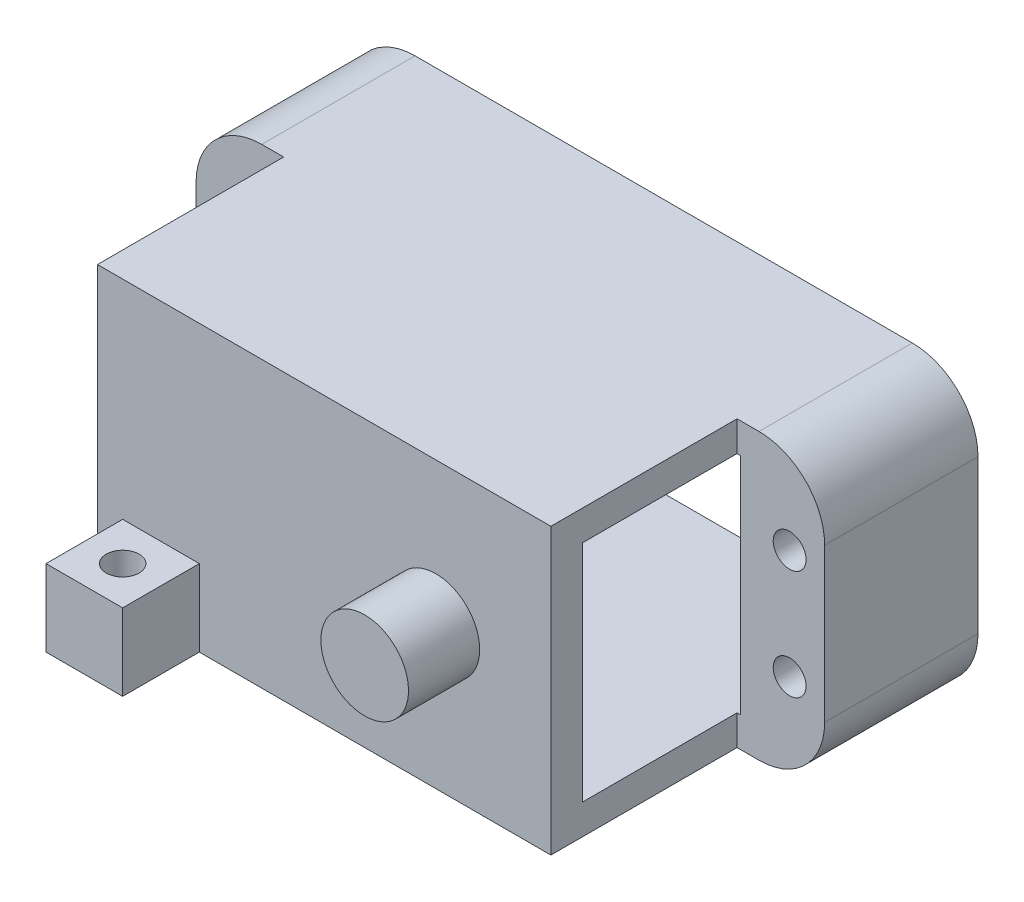
SolidWorks part; units mm, degrees
ref_plane "Front Plane" through (0, 0, 0) normal (0, 0, 1) x (1, 0, 0)
ref_plane "Top Plane" through (0, 0, 0) normal (0, 1, 0) x (1, 0, 0)
ref_plane "Right Plane" through (0, 0, 0) normal (1, 0, 0) x (0, 0, -1)
ref_plane "Plane4" through (0, 0, 0) normal (0, 0, -1) x (-1, 0, 0)
sketch "Sketch1" plane through (0, 0, 0) normal (0, 0, -1) x (-1, 0, 0)
  line L0 (-21, 13) -> (-21, -13)
  line L1 (-21, -13) -> (28.7, -13)
  line L2 (28.7, -13) -> (28.7, 13)
  line L3 (28.7, 13) -> (-21, 13)
extrude "Boss-Extrude1" add sketch "Sketch1" against normal blind 14
sketch "Sketch2" plane through (0, 0, 14) normal (0, 0, 1) x (1, 0, 0)
  line L0 (20.7, 13) -> (20.7, -13)
  line L1 (20.7, -13) -> (-20.7, -13)
  line L2 (-20.7, -13) -> (-20.7, 13)
  line L3 (-20.7, 13) -> (20.7, 13)
extrude "Boss-Extrude2" add sketch "Sketch2" along normal blind 17
ref_plane "Plane5" through (0, 10.25, 0) normal (0, 1, 0) x (1, 0, 0)
sketch "Sketch3" plane through (0, 10.25, 0) normal (0, 1, 0) x (1, 0, 0)
  line L0 (20.7, -14) -> (21, -14)
  line L1 (21, -14) -> (21, 0)
  line L2 (21, 0) -> (-21, 0)
  line L3 (-21, 0) -> (-21, -14)
  line L4 (-21, -14) -> (-20.7, -14)
  line L5 (-20.7, -14) -> (-20.7, -28.1)
  line L6 (-20.7, -28.1) -> (20.7, -28.1)
  line L7 (20.7, -28.1) -> (20.7, -14)
extrude "Cut-Extrude1" cut sketch "Sketch3" against normal blind 20.5
sketch "Sketch4" plane through (21, 0, 0) normal (1, 0, 0) x (0, 0, -1)
  line L0 (-14, -13) -> (-14, 13)
  line L1 (-14, 13) -> (0, 13)
  line L2 (0, 13) -> (0, -13)
  line L3 (0, -13) -> (-14, -13)
extrude "Boss-Extrude3" add sketch "Sketch4" along normal blind 7.7
sketch "Sketch5" plane through (0, 0, 31) normal (0, 0, 1) x (1, 0, 0)
  line L0 (-18.4, 13) -> (-11.4, 13)
  line L1 (-11.4, 13) -> (-11.4, 6)
  line L2 (-11.4, 6) -> (-18.4, 6)
  line L3 (-18.4, 6) -> (-18.4, 13)
  line L4 (0, 0) -> (-20.7, 0) construction
  line L5 (-20.7, 13) -> (-20.7, -13) construction
  line L6 (-18.4, -13) -> (-11.4, -13)
  line L7 (-18.4, -6) -> (-18.4, -13)
  line L8 (-11.4, -6) -> (-18.4, -6)
  line L9 (-11.4, -13) -> (-11.4, -6)
sketch "Sketch6" plane through (0, 13, 0) normal (0, 1, 0) x (-1, 0, 0)
  line L0 (10.4, 0) -> (2.4, 0)
  line L1 (2.4, 0) -> (2.4, 5)
  line L2 (2.4, 5) -> (10.4, 5)
  line L3 (10.4, 5) -> (10.4, 0)
extrude "Boss-Extrude5" add sketch "Sketch6" against normal blind 7 from surface at -26 starting at face at (0, -13, 14.75)
ref_plane "Plane6" through (0, 0, 0) normal (0, -1, 0) x (1, 0, 0)
extrude "Boss-Extrude6" add sketch "Sketch5" along normal blind 7 contours L7 L6 L9 L8
sketch "Sketch7" plane through (0, 0, 0) normal (0, -1, 0) x (1, 0, 0)
  line L0 (14.2, 37.5) -> (10.2, 37.5)
  line L1 (10.2, 37.5) -> (10.2, 31)
  line L2 (10.2, 31) -> (14.2, 31)
  line L3 (14.2, 31) -> (14.2, 37.5)
  line L4 (10.2, 37.5) -> (10.2, 31) construction
revolve "Revolve1" add sketch "Sketch7" angle 360 about L4
hole_wizard "Ø3.0 (3) Diameter Hole1" positions "Sketch9" profile "Sketch8" hole size "Ø3.0" standard "ANSI Metric"
sketch "Sketch9" plane through (0, 0, 0) normal (0, 0, -1) x (-1, 0, 0)
  point P0 (-25.5, -5)
  point P1 (-25.5, 5)
  point P2 (25.5, -5)
  point P3 (25.5, 5)
sketch "Sketch8" plane through (25.5, -5, 0) normal (1, 0, 0) x (0, 1, 0)
  line L0 (0, 0) -> (0, 38)
  line L1 (0, 38) -> (1.5, 38)
  line L2 (1.5, 38) -> (1.5, 0)
  line L5 (1.5, 0) -> (0, 0)
  line L11 (0, -6.35) -> (0, 107.95) construction
  dimension "Thru Hole Dia." = 3
  dimension "Thru Hole Depth" = 38
hole_wizard "Ø3.0 (3) Diameter Hole2" positions "Sketch11" profile "Sketch10" hole size "Ø3.0" standard "ANSI Metric"
sketch "Sketch11" plane through (-10.4, 0, 0) normal (-1, 0, 0) x (0, 0, 1)
  line L0 (14, -13) -> (0, -13) construction
  point P0 (2.2, -16.5)
  point P1 (0, 0)
  dimension "D1" = 3.5
sketch "Sketch10" plane through (-10.4, -16.5, 2.2) normal (0, 1, 0) x (0, 0, 1)
  line L0 (0, 0) -> (0, 39.1)
  line L1 (0, 39.1) -> (1.5, 39.1)
  line L2 (1.5, 39.1) -> (1.5, 0)
  line L5 (1.5, 0) -> (0, 0)
  line L11 (0, -6.35) -> (0, 107.95) construction
  dimension "Thru Hole Dia." = 3
  dimension "Thru Hole Depth" = 39.1
hole_wizard "Ø3.0 (3) Diameter Hole3" positions "Sketch13" profile "Sketch12" hole size "Ø3.0" standard "ANSI Metric"
sketch "Sketch13" plane through (0, 13, 0) normal (0, 1, 0) x (1, 0, 0)
  point P0 (-14.9, -34.5)
sketch "Sketch12" plane through (-14.9, 13, 34.5) normal (1, 0, 0) x (0, 0, 1)
  line L0 (0, 0) -> (0, 33)
  line L1 (0, 33) -> (1.5, 33)
  line L2 (1.5, 33) -> (1.5, 0)
  line L5 (1.5, 0) -> (0, 0)
  line L11 (0, -6.35) -> (0, 107.95) construction
  dimension "Thru Hole Dia." = 3
  dimension "Thru Hole Depth" = 33
fillet "Fillet1" radius 6 4 edges at (28.7, 13, 7) (28.7, -13, 7) (-28.7, 13, 7) (-28.7, -13, 7)
